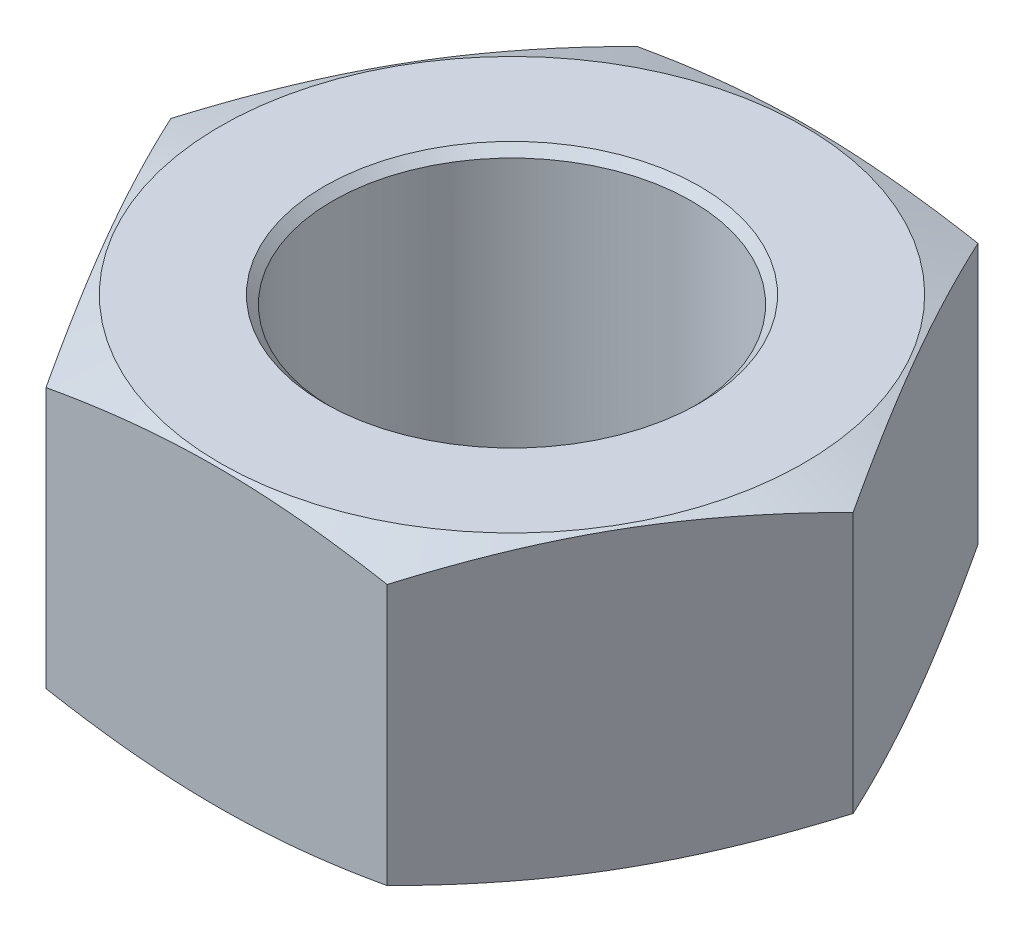
SolidWorks part; units mm, degrees
material "AISI 1020"
ref_plane "Plano superior" through (0, 0, 0) normal (0, 0, 1) x (1, 0, 0)
ref_plane "Plano frontal" through (0, 0, 0) normal (0, 1, 0) x (1, 0, 0)
ref_plane "Plano direito" through (0, 0, 0) normal (1, 0, 0) x (0, 0, -1)
sketch "Esboço1" plane through (0, 0, 0) normal (0, 1, 0) x (1, 0, 0)
  line L1 (4.0415, 7) -> (-4.0415, 7)
  line L2 (-4.0415, 7) -> (-8.0829, 0)
  line L3 (-8.0829, 0) -> (-4.0415, -7)
  line L4 (-4.0415, -7) -> (4.0415, -7)
  line L5 (4.0415, -7) -> (8.0829, 0)
  line L6 (8.0829, 0) -> (4.0415, 7)
  circle A0 centre (0, 0) radius 7 construction
  dimension "D1" = 14
extrude "Ressalto-extrusão2" add sketch "Esboço1" along normal blind 7
hole_wizard "Furo roscado de M101" positions "Esboço3" profile "Esboço4" tap size "M10" standard "DIN" end condition up to next
sketch "Esboço3" plane through (0, 0, 0) normal (0, -1, 0) x (-1, 0, 0)
  point P0 (0, 0)
sketch "Esboço4" plane through (0, 0, 0) normal (1, 0, 0) x (0, 0, -1)
  line L0 (0, 0) -> (0, 7)
  line L1 (0, 7) -> (4.25, 7)
  line L2 (4.25, 7) -> (4.25, 0.775)
  line L3 (4.25, 0.775) -> (5.025, 0)
  line L5 (5.025, 0) -> (0, 0)
  line L6 (-4.25, 0.775) -> (-5.025, 0) construction
  line L11 (0, -6.35) -> (0, 107.95) construction
  dimension "Thru Tap Drill Dia." = 8.5
  dimension "Thru Tap Drill Depth" = 7
  dimension "Near C'Sink Dia." = 10.05
  dimension "Near C'Sink Angle" = 90
cosmetic thread "Rosca de furo1" parameters "D2"=10
cosmetic thread "Representação de rosca1" parameters "D2"=10
chamfer "Chanfro2" distance 0.2 angle 45 1 edges at (0, 7, 4.25)
sketch "Esboço5" plane through (0, 7, 0) normal (0, 1, 0) x (1, 0, 0)
  circle A0 centre (0, 0) radius 6.9143
extrude "Corte-extrusão1" cut sketch "Esboço5" against normal blind 13 draft 70 flip side to cut
sketch "Esboço6" plane through (0, 0, 0) normal (0, -1, 0) x (1, 0, 0)
  circle A0 centre (0, 0) radius 6.9948
extrude "Corte-extrusão2" cut sketch "Esboço6" against normal blind 13 draft 70 flip side to cut
